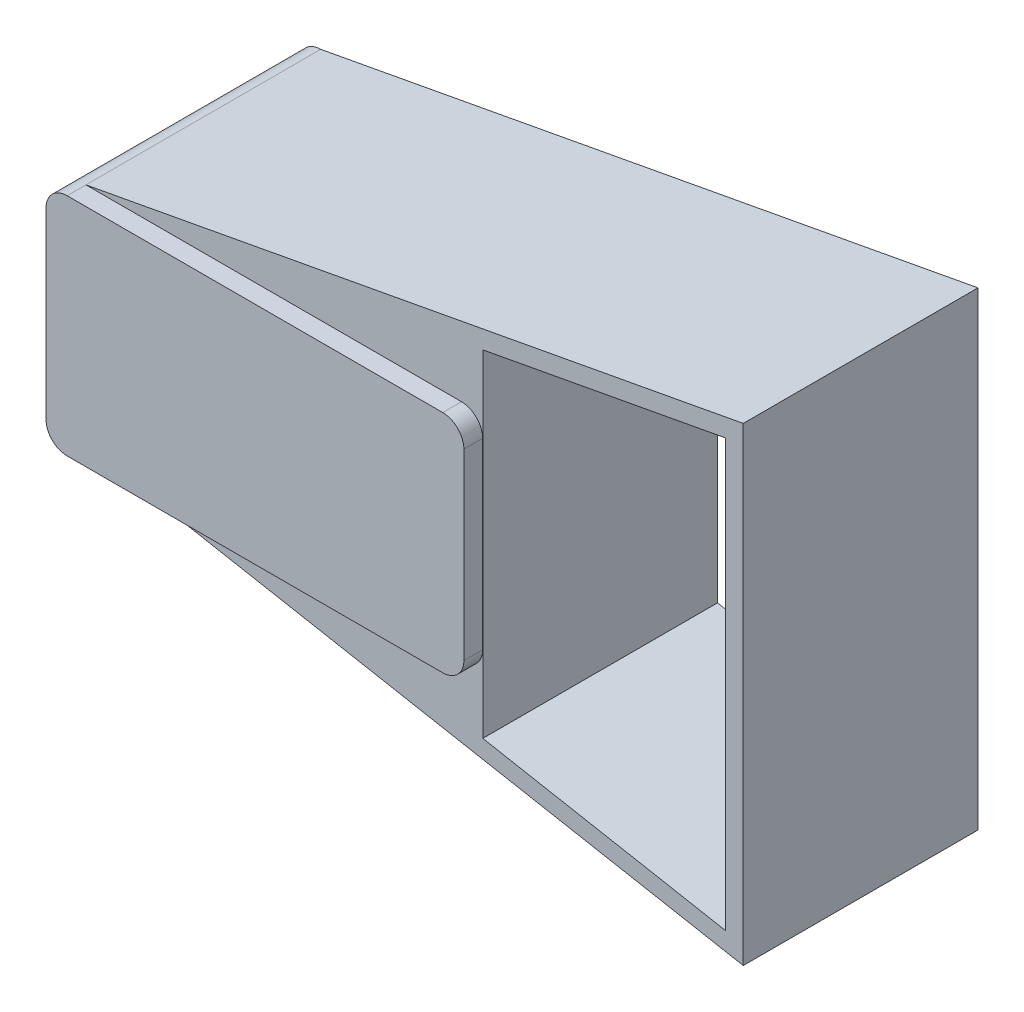
SolidWorks part; units mm, degrees
ref_plane "Plan de face" through (0, 0, 0) normal (0, 0, 1) x (1, 0, 0)
ref_plane "Plan de dessus" through (0, 0, 0) normal (0, 1, 0) x (1, 0, 0)
ref_plane "Plan de droite" through (0, 0, 0) normal (1, 0, 0) x (0, 0, -1)
sketch "Esquisse1" plane through (0, 0, 0) normal (0, 0, 1) x (1, 0, 0)
  line L0 (20, 2) -> (-20, 2)
  line L1 (-22.25, -0.25) -> (-22.25, -19.75)
  line L2 (-20, -22) -> (20, -22)
  line L3 (22.25, -19.75) -> (22.25, -0.25)
  arc A0 (-20, 2) -> (-22.25, -0.25) centre (-20, -0.25) ccw
  arc A1 (-22.25, -19.75) -> (-20, -22) centre (-20, -19.75) ccw
  arc A2 (20, -22) -> (22.25, -19.75) centre (20, -19.75) ccw
  arc A3 (22.25, -0.25) -> (20, 2) centre (20, -0.25) ccw
extrude "Boss.-Extru.1" add sketch "Esquisse1" along normal blind 2
sketch "Esquisse2" plane through (0, 0, 0) normal (0, 0, -1) x (-1, 0, 0)
  line L0 (-20.35, -0.25) -> (-20.35, -19.75)
  line L1 (-20, -20.1) -> (20, -20.1)
  line L2 (20.35, -19.75) -> (20.35, -0.25)
  line L3 (20, 0.1) -> (-20, 0.1)
  line L4 (-22.25, -0.25) -> (-22.25, -19.75)
  line L5 (-20, -22) -> (20, -22)
  line L6 (22.25, -19.75) -> (22.25, -0.25)
  line L7 (20, 2) -> (-20, 2)
  line L10 (22.25, -19.75) -> (22.25, -0.25)
  line L13 (-50, 2) -> (-50, -22)
  line L15 (-50, -35) -> (-50, 15)
  line L16 (-22.25, -0.25) -> (-22.25, -19.75) construction
  line L17 (20, 2) -> (-20, 2) construction
  line L18 (-20, -22) -> (20, -22) construction
  line L19 (-50, 15) -> (20, 2)
  line L20 (-50, -35) -> (20, -22)
  arc A0 (-20, 0.1) -> (-20.35, -0.25) centre (-20, -0.25) ccw
  arc A1 (-20.35, -19.75) -> (-20, -20.1) centre (-20, -19.75) ccw
  arc A2 (20, -20.1) -> (20.35, -19.75) centre (20, -19.75) ccw
  arc A3 (20.35, -0.25) -> (20, 0.1) centre (20, -0.25) ccw
  arc A4 (-20, 2) -> (-22.25, -0.25) centre (-20, -0.25) ccw
  arc A5 (-22.25, -19.75) -> (-20, -22) centre (-20, -19.75) ccw
  arc A6 (20, -22) -> (22.25, -19.75) centre (20, -19.75) ccw
  arc A7 (22.25, -0.25) -> (20, 2) centre (20, -0.25) ccw
  arc A10 (20, -22) -> (22.25, -19.75) centre (20, -19.75) ccw
  arc A11 (22.25, -0.25) -> (20, 2) centre (20, -0.25) ccw
  arc A16 (-20, 2) -> (-22.25, -0.25) centre (-20, -0.25) ccw construction
  arc A17 (-22.25, -19.75) -> (-20, -22) centre (-20, -19.75) ccw construction
  point P29 (-50, -10)
  point P30 (-50, -10)
  arc M9 (-20, 2) -> (-22.25, -0.25) centre (-20, -0.25) ccw
  line M10 (-22.25, -0.25) -> (-22.25, -19.75)
  arc M11 (-22.25, -19.75) -> (-20, -22) centre (-20, -19.75) ccw
  line M12 (-20, -22) -> (20, -22)
  arc M13 (20, -22) -> (22.25, -19.75) centre (20, -19.75) ccw
  line M14 (22.25, -19.75) -> (22.25, -0.25)
  arc M15 (22.25, -0.25) -> (20, 2) centre (20, -0.25) ccw
  line M16 (20, 2) -> (-20, 2)
  dimension "D3" = 70
  dimension "D1" = 0
  dimension "D2" = 1.9
extrude "Boss.-Extru.3" add sketch "Esquisse2" along normal blind 25 contours L15 L20 L19 L13 M12 M11 M10 M9 M16 | A3 L2 A2 L1 A1 L0 A0 L3 M16 M9 M10 M11 M12 M13 M14 M15
sketch "Esquisse5" plane through (0, 0, -25) normal (0, 0, -1) x (-1, 0, 0)
  line L6 (-22.2642, 7.9166) -> (-22.2642, -27.9166)
  line L8 (-48.1, -32.7147) -> (19.9014, -20.0858)
  line L9 (20.35, -19.75) -> (20.35, -0.25)
  line L10 (19.9014, 0.0858) -> (-48.1, 12.7147)
  line L11 (-48.1, 12.7147) -> (-48.1, -32.7147)
  line L12 (-48.1, -32.7147) -> (-22.2642, -27.9166)
  line L13 (20.35, -19.75) -> (20.35, -0.25)
  line L14 (-22.2642, 7.9166) -> (-48.1, 12.7147)
  line L15 (-48.1, 12.7147) -> (-48.1, -32.7147)
  arc A4 (19.9014, -20.0858) -> (20.35, -19.75) centre (20, -19.75) ccw
  arc A5 (20.35, -0.25) -> (19.9014, 0.0858) centre (20, -0.25) ccw
  arc A6 (19.9014, -20.0858) -> (20.35, -19.75) centre (20, -19.75) ccw
  arc A7 (20.35, -0.25) -> (19.9014, 0.0858) centre (20, -0.25) ccw
  point P3 (-20.3642, -9.9987)
  dimension "D1" = 1.9
extrude "Enlèv. mat.-Extru.1" cut sketch "Esquisse5" against normal blind 50 contours L14 L15 L12 L6
